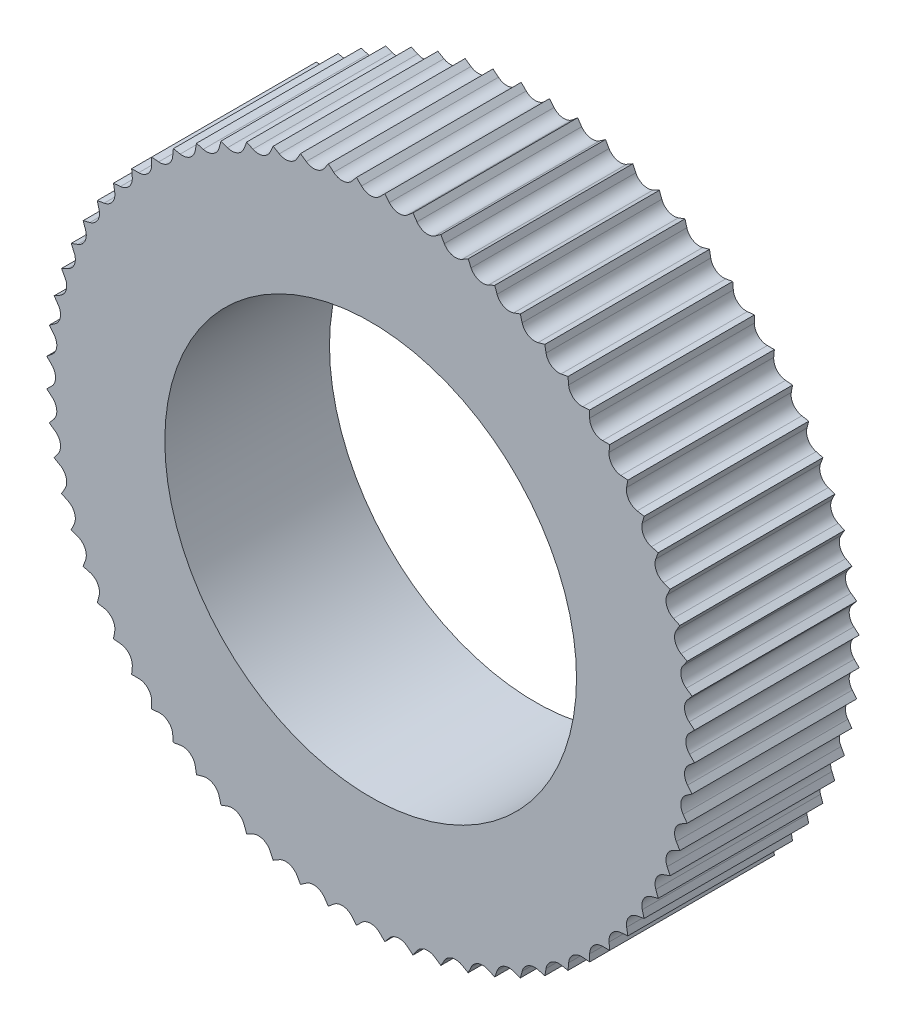
SolidWorks part; units mm, degrees
ref_plane "Front Plane" through (0, 0, 0) normal (0, 0, 1) x (1, 0, 0)
ref_plane "Top Plane" through (0, 0, 0) normal (0, 1, 0) x (1, 0, 0)
ref_plane "Right Plane" through (0, 0, 0) normal (1, 0, 0) x (0, 0, -1)
sketch "Sketch1" plane through (0, 0, 0) normal (0, 0, 1) x (1, 0, 0)
  circle A0 centre (0, 0) radius 12.5
  circle A1 centre (0, 0) radius 6.35
  dimension "D1" = 12.7
  dimension "D2" = 25
extrude "Boss-Extrude1" add sketch "Sketch1" along normal blind 5.08
sketch "Sketch2" plane through (0, 0, 5.08) normal (0, 0, 1) x (1, 0, 0)
  line L0 (-2.6595, 12.2138) -> (-0.2828, 9.8371)
  line L1 (0.2828, 9.8371) -> (2.6595, 12.2138)
  line L2 (0, 9.72) -> (0, 0) construction
  line L3 (0, 0) -> (0.8472, 9.683) construction
  line L4 (-1.5849, 12.3991) -> (0.5756, 9.8243) construction
  line L5 (1.1391, 9.775) -> (3.7139, 11.9355) construction
  line L6 (-2.6595, 12.2138) -> (2.6595, 12.2138) construction
  line L7 (-1.5849, 12.3991) -> (3.7139, 11.9355) construction
  arc A0 (-0.2828, 9.8371) -> (0.2828, 9.8371) centre (0, 10.12) ccw
  circle A1 centre (0, 0) radius 12.5
  arc A2 (2.6595, 12.2138) -> (-2.6595, 12.2138) centre (0, 0) ccw
  circle A3 centre (0, 0) radius 12.5 construction
  arc A4 (0.5756, 9.8243) -> (1.1391, 9.775) centre (0.882, 10.0815) ccw construction
  point P4 (0, 12.5)
  point P9 (0.4362, 9.9905)
  point P14 (0.8472, 9.683)
  point P15 (0, 9.72)
  point P18 (-1.5849, 12.3991)
  point P19 (0, 0)
  dimension "D2" = 0.4
  dimension "D3" = 90
  dimension "D4" = 10
  dimension "D5" = 5
  dimension "D1" = 0
extrude "Cut-Extrude1" cut sketch "Sketch2" against normal through all
pattern_circular "CirPattern1" count 72 over 360 about axis through (0, 0, 0) along (0, 0, 1) of "Cut-Extrude1"
